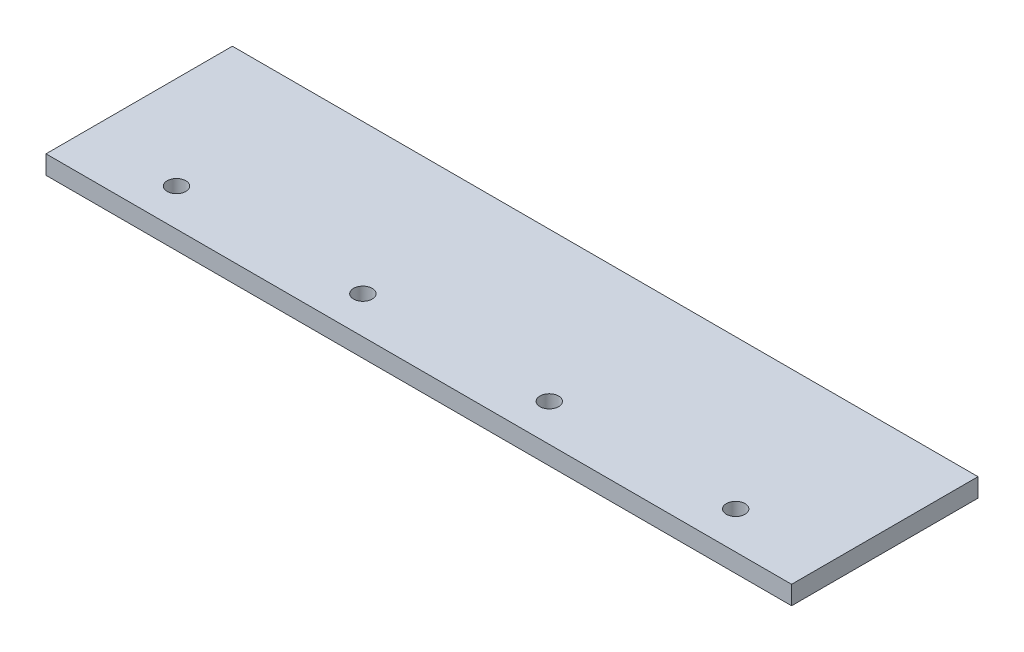
SolidWorks part; units mm, degrees
ref_plane "Front Plane" through (0, 0, 0) normal (0, 0, 1) x (1, 0, 0)
ref_plane "Top Plane" through (0, 0, 0) normal (0, 1, 0) x (1, 0, 0)
ref_plane "Right Plane" through (0, 0, 0) normal (1, 0, 0) x (0, 0, -1)
sketch "Sketch2" plane through (0, 0, 0) normal (0, 1, 0) x (1, 0, 0)
  line L0 (0, -15) -> (0, 15) construction
  line L1 (-60, 15) -> (60, 15)
  line L2 (-60, 15) -> (-60, -15)
  line L3 (-60, -15) -> (60, -15)
  line L4 (60, 15) -> (60, -15)
  line L5 (-60, 15) -> (60, -15) construction
  line L6 (-60, -15) -> (60, 15) construction
  line L7 (-45, -15) -> (-45, -9) construction
  circle A0 centre (-45, -9) radius 1.5
  circle A1 centre (-15, -9) radius 1.5
  circle A2 centre (15, -9) radius 1.5
  circle A3 centre (45, -9) radius 1.5
  point P0 (0, 0)
  dimension "D1" = 3
  dimension "D4" = 6
  dimension "D2" = 120
  dimension "D5" = 45
  dimension "D6" = 30
  dimension "D3" = 4
extrude "Boss-Extrude1" add sketch "Sketch2" along normal blind 3
